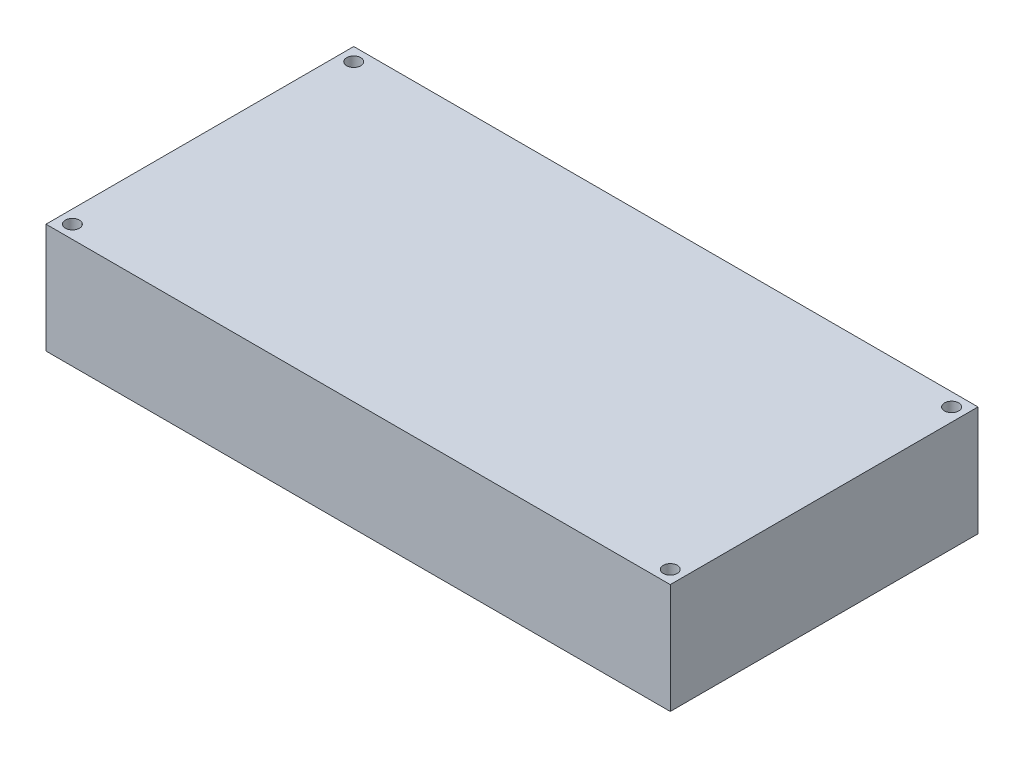
SolidWorks part; units mm, degrees
ref_plane "Front" through (0, 0, 0) normal (0, 0, 1) x (1, 0, 0)
ref_plane "Top" through (0, 0, 0) normal (0, 1, 0) x (1, 0, 0)
ref_plane "Right" through (0, 0, 0) normal (1, 0, 0) x (0, 0, -1)
sketch "Sketch1" plane through (0, 0, 0) normal (0, 1, 0) x (1, 0, 0)
  line L0 (-107.95, 50.8) -> (107.95, -50.8) construction
  line L1 (112.7125, -55.5625) -> (-112.7125, -55.5625)
  line L2 (112.7125, -55.5625) -> (112.7125, 55.5625)
  line L3 (112.7125, 55.5625) -> (-112.7125, 55.5625)
  line L4 (-112.7125, -55.5625) -> (-112.7125, 55.5625)
  line L5 (112.7125, -55.5625) -> (-112.7125, 55.5625) construction
  line L6 (112.7125, 55.5625) -> (-112.7125, -55.5625) construction
  circle A0 centre (-107.95, 50.8) radius 2.5527
  circle A1 centre (107.95, 50.8) radius 2.5527
  circle A2 centre (107.95, -50.8) radius 2.5527
  circle A3 centre (-107.95, -50.8) radius 2.5527
  point P0 (0, 0)
  dimension "D1" = 215.9
  dimension "D2" = 101.6
  dimension "D5" = 5.1054
  dimension "D3" = 225.425
  dimension "D4" = 111.125
extrude "Boss-Extrude1" add sketch "Sketch1" along normal blind 39.6875
